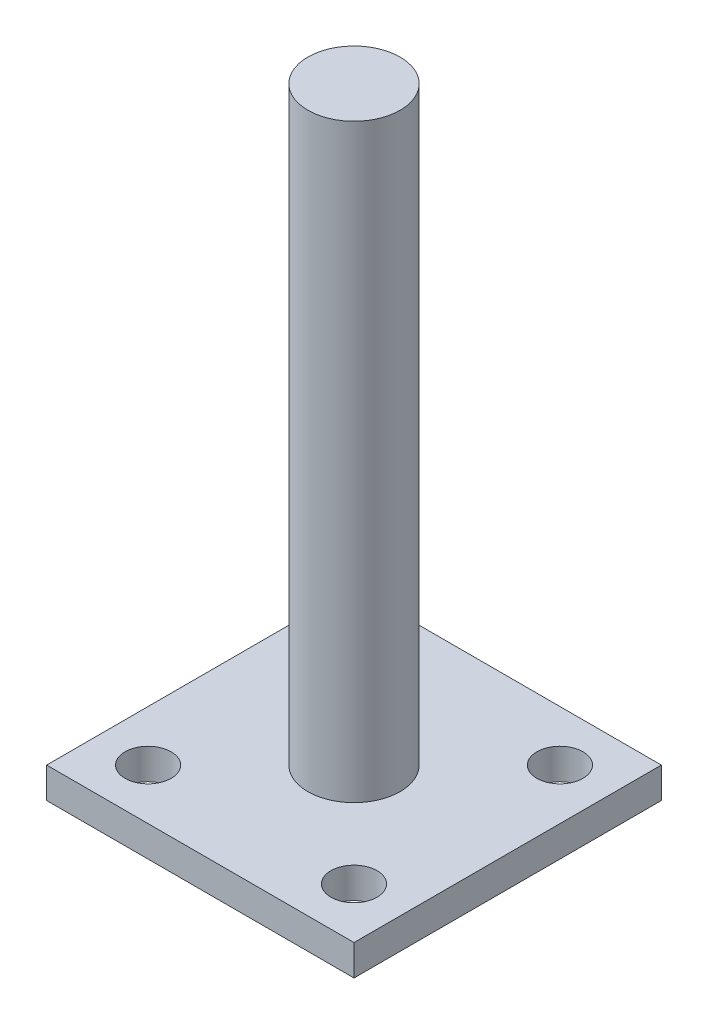
SolidWorks part; units mm, degrees
ref_plane "Front Plane" through (0, 0, 0) normal (0, 0, 1) x (1, 0, 0)
ref_plane "Top Plane" through (0, 0, 0) normal (0, 1, 0) x (1, 0, 0)
ref_plane "Right Plane" through (0, 0, 0) normal (1, 0, 0) x (0, 0, -1)
sketch "Sketch1" plane through (0, 0, 0) normal (0, 1, 0) x (1, 0, 0)
  line L1 (50, 50) -> (-50, 50)
  line L2 (50, 50) -> (50, -50)
  line L3 (50, -50) -> (-50, -50)
  line L4 (-50, 50) -> (-50, -50)
  line L5 (50, 50) -> (-50, -50) construction
  line L6 (50, -50) -> (-50, 50) construction
  line L7 (-33.5, -33.5) -> (33.5, -33.5) construction
  line L8 (-33.5, -33.5) -> (-33.5, 33.5) construction
  line L9 (-33.5, 33.5) -> (33.5, 33.5) construction
  line L10 (33.5, -33.5) -> (33.5, 33.5) construction
  line L11 (-33.5, -33.5) -> (33.5, 33.5) construction
  line L12 (-33.5, 33.5) -> (33.5, -33.5) construction
  circle A0 centre (33.5, 33.5) radius 7.5
  circle A1 centre (-33.5, 33.5) radius 7.5
  circle A2 centre (-33.5, -33.5) radius 7.5
  circle A3 centre (33.5, -33.5) radius 7.5
  point P0 (0, 0)
  point P6 (0, 0)
  point P15 (-33.69, -33.69)
  dimension "D1" = 15
  dimension "D2" = 100
  dimension "D3" = 67
extrude "Boss-Extrude1" add sketch "Sketch1" along normal blind 10
sketch "Sketch2" plane through (0, 10, 0) normal (0, 1, 0) x (1, 0, 0)
  circle A0 centre (0, 0) radius 15
  dimension "D1" = 30
extrude "Boss-Extrude2" add sketch "Sketch2" along normal blind 192
